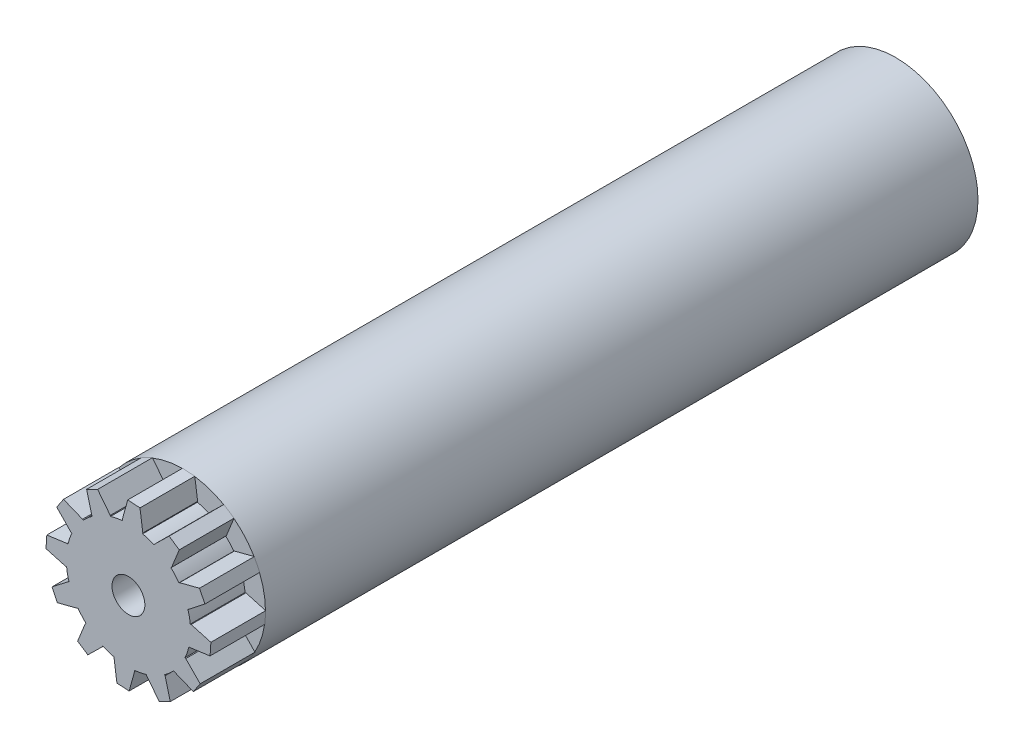
SolidWorks part; units mm, degrees
ref_plane "Front Plane" through (0, 0, 0) normal (0, 0, 1) x (1, 0, 0)
ref_plane "Top Plane" through (0, 0, 0) normal (0, 1, 0) x (1, 0, 0)
ref_plane "Right Plane" through (0, 0, 0) normal (1, 0, 0) x (0, 0, -1)
sketch "Sketch1" plane through (0, 0, 0) normal (0, 0, 1) x (1, 0, 0)
  circle A0 centre (0, 0) radius 7.5
  dimension "D1" = 15
extrude "Boss-Extrude1" add sketch "Sketch1" along normal blind 65
sketch "Sketch3" plane through (0, 0, 0) normal (0, 1, 0) x (1, 0, 0)
  line L0 (0, -64.3503) -> (0, -66.8083) construction
sketch "Sketch4" plane through (0, 0, 65) normal (0, 0, 1) x (1, 0, 0)
  line L0 (-0.5637, 5.7154) -> (1.3125, 5.5911) construction
  line L1 (1.3125, 5.5911) -> (1.0527, 7.4467)
  line L2 (1.0527, 7.4467) -> (-0.0614, 7.5205)
  line L3 (-0.0614, 7.5205) -> (-0.5637, 5.7154)
  line L4 (-0.5637, 5.7154) -> (0, 0)
  line L5 (0, 0) -> (1.3125, 5.5911)
  line L6 (0, 0) -> (3.9322, 4.1858)
  line L7 (3.9322, 4.1858) -> (4.635, 5.9227)
  line L8 (4.635, 5.9227) -> (3.7071, 6.5436)
  line L9 (3.7071, 6.5436) -> (2.3695, 5.2315)
  line L10 (2.3695, 5.2315) -> (0, 0)
  line L11 (0, 0) -> (5.4983, 1.6589)
  line L12 (5.4983, 1.6589) -> (6.9754, 2.8117)
  line L13 (6.9754, 2.8117) -> (6.4823, 3.8134)
  line L14 (6.4823, 3.8134) -> (4.6678, 3.3458)
  line L15 (4.6678, 3.3458) -> (0, 0)
  line L16 (0, 0) -> (5.5911, -1.3125)
  line L17 (5.5911, -1.3125) -> (7.4467, -1.0527)
  line L18 (7.4467, -1.0527) -> (7.5205, 0.0614)
  line L19 (7.5205, 0.0614) -> (5.7154, 0.5637)
  line L20 (5.7154, 0.5637) -> (0, 0)
  line L21 (0, 0) -> (4.1858, -3.9322)
  line L22 (4.1858, -3.9322) -> (5.9227, -4.635)
  line L23 (5.9227, -4.635) -> (6.5436, -3.7071)
  line L24 (6.5436, -3.7071) -> (5.2315, -2.3695)
  line L25 (5.2315, -2.3695) -> (0, 0)
  line L26 (0, 0) -> (1.6589, -5.4983)
  line L27 (1.6589, -5.4983) -> (2.8117, -6.9754)
  line L28 (2.8117, -6.9754) -> (3.8134, -6.4823)
  line L29 (3.8134, -6.4823) -> (3.3458, -4.6678)
  line L30 (3.3458, -4.6678) -> (0, 0)
  line L31 (0, 0) -> (-1.3125, -5.5911)
  line L32 (-1.3125, -5.5911) -> (-1.0527, -7.4467)
  line L33 (-1.0527, -7.4467) -> (0.0614, -7.5205)
  line L34 (0.0614, -7.5205) -> (0.5637, -5.7154)
  line L35 (0.5637, -5.7154) -> (0, 0)
  line L36 (0, 0) -> (-3.9322, -4.1858)
  line L37 (-3.9322, -4.1858) -> (-4.635, -5.9227)
  line L38 (-4.635, -5.9227) -> (-3.7071, -6.5436)
  line L39 (-3.7071, -6.5436) -> (-2.3695, -5.2315)
  line L40 (-2.3695, -5.2315) -> (0, 0)
  line L41 (0, 0) -> (-5.4983, -1.6589)
  line L42 (-5.4983, -1.6589) -> (-6.9754, -2.8117)
  line L43 (-6.9754, -2.8117) -> (-6.4823, -3.8134)
  line L44 (-6.4823, -3.8134) -> (-4.6678, -3.3458)
  line L45 (-4.6678, -3.3458) -> (0, 0)
  line L46 (0, 0) -> (-5.5911, 1.3125)
  line L47 (-5.5911, 1.3125) -> (-7.4467, 1.0527)
  line L48 (-7.4467, 1.0527) -> (-7.5205, -0.0614)
  line L49 (-7.5205, -0.0614) -> (-5.7154, -0.5637)
  line L50 (-5.7154, -0.5637) -> (0, 0)
  line L51 (0, 0) -> (-4.1858, 3.9322)
  line L52 (-4.1858, 3.9322) -> (-5.9227, 4.635)
  line L53 (-5.9227, 4.635) -> (-6.5436, 3.7071)
  line L54 (-6.5436, 3.7071) -> (-5.2315, 2.3695)
  line L55 (-5.2315, 2.3695) -> (0, 0)
  line L56 (0, 0) -> (-1.6589, 5.4983)
  line L57 (-1.6589, 5.4983) -> (-2.8117, 6.9754)
  line L58 (-2.8117, 6.9754) -> (-3.8134, 6.4823)
  line L59 (-3.8134, 6.4823) -> (-3.3458, 4.6678)
  line L60 (-3.3458, 4.6678) -> (0, 0)
  line L61 (-1.6589, 5.4983) -> (-0.5637, 5.7154)
  circle A0 centre (0, 0) radius 5.6656
  circle A1 centre (0, 0) radius 7.5 construction
  point P55 (0, 0)
  dimension "D1" = 12
extrude "Boss-Extrude7" add sketch "Sketch4" along normal blind 5 contours L5 A0 L4 | L46 L47 L48 L49 L50 | L51 L52 L53 L54 L55 | L6 L7 L8 L9 L10 | L11 L12 L13 L14 L15 | L16 L17 L18 L19 L20 | L21 L22 L23 L24 L25 | L26 L27 L28 L29 L30 | L31 L32 L33 L34 L35 | L36 L37 L38 L39 L40 | L41 L42 L43 L44 L45 | L56 L57 L58 L59 L60
sketch "Sketch5" plane through (0, 0, 0) normal (0, 0, -1) x (-1, 0, 0)
  circle A0 centre (0, 0) radius 1.5
  dimension "D1" = 3
extrude "Cut-Extrude1" cut sketch "Sketch5" against normal through all
